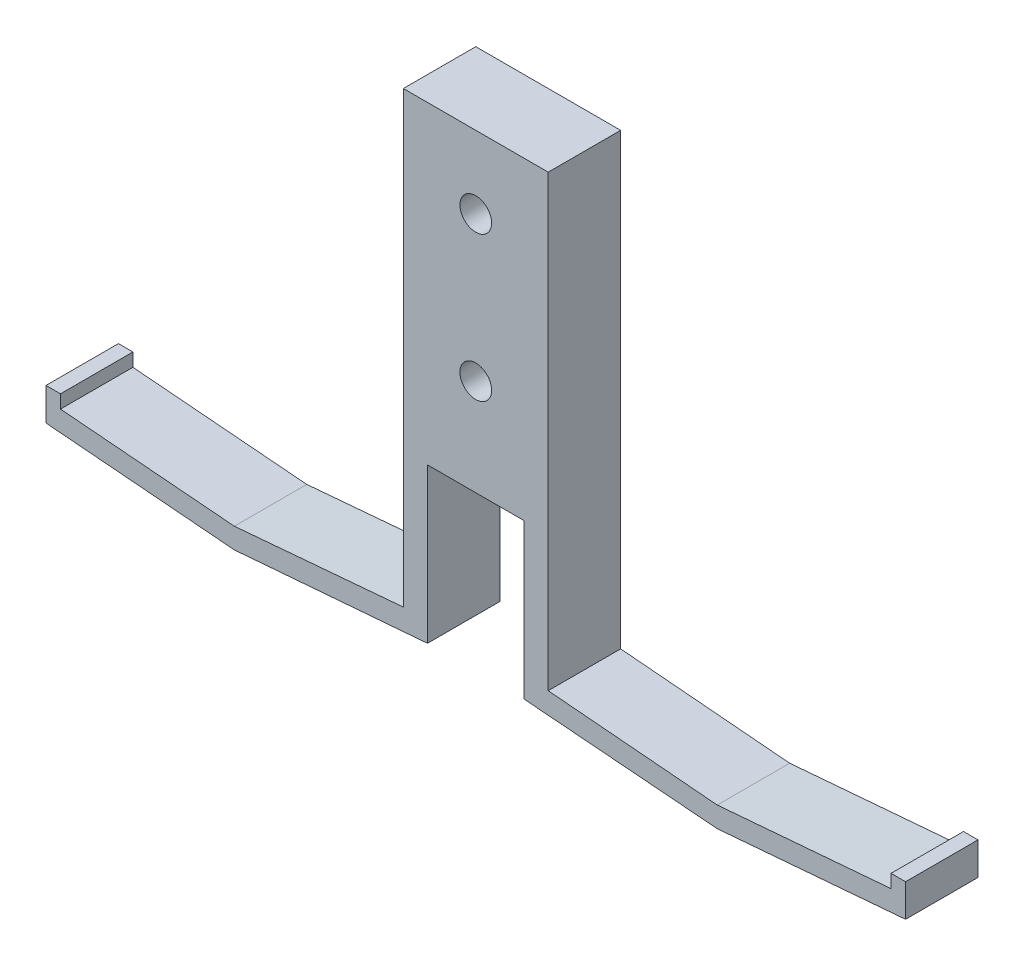
SolidWorks part; units mm, degrees
ref_plane "Front Plane" through (0, 0, 0) normal (0, 0, 1) x (1, 0, 0)
ref_plane "Top Plane" through (0, 0, 0) normal (0, 1, 0) x (1, 0, 0)
ref_plane "Right Plane" through (0, 0, 0) normal (1, 0, 0) x (0, 0, -1)
sketch "Sketch2" plane through (0, 0, 0) normal (0, 0, 1) x (1, 0, 0)
  line L1 (12.7, 0) -> (12.7, -40.64)
  line L2 (12.7, -40.64) -> (63.5, -44.7675)
  line L3 (63.5, -44.7675) -> (113.03, -40.64)
  line L4 (113.03, -40.64) -> (113.03, -32.0675)
  line L5 (109.22, -32.0675) -> (109.22, -35.56)
  line L6 (109.22, -35.56) -> (63.5, -39.37)
  line L19 (113.03, -32.0675) -> (109.22, -32.0675)
  line L20 (0, 125.2351) -> (0, -75.9356) construction
  line L21 (12.7, 0) -> (-12.7, 0)
  line L22 (0, 0) -> (0, 82.55)
  line L23 (19.05, 82.55) -> (-19.05, 82.55)
  line L24 (19.05, 82.55) -> (19.05, 0)
  line L25 (19.05, 0) -> (19.05, -35.56)
  line L26 (19.05, -35.56) -> (63.5, -39.37)
  line L27 (-19.05, 0) -> (-19.05, -35.56)
  line L28 (-19.05, 82.55) -> (-19.05, 0)
  line L29 (-12.7, 0) -> (-12.7, -40.64)
  line L30 (-12.7, -40.64) -> (-63.5, -44.7675)
  line L31 (-63.5, -44.7675) -> (-113.03, -40.64)
  line L32 (-113.03, -40.64) -> (-113.03, -32.0675)
  line L33 (-113.03, -32.0675) -> (-109.22, -32.0675)
  line L34 (-109.22, -32.0675) -> (-109.22, -35.56)
  line L35 (-109.22, -35.56) -> (-63.5, -39.37)
  line L36 (-19.05, -35.56) -> (-63.5, -39.37)
  dimension "D1" = 19.05
  dimension "D2" = 12.7
  dimension "D3" = 35.56
  dimension "D4" = 3.81
  dimension "D5" = 40.64
  dimension "D6" = 3.81
  dimension "D7" = 45.72
  dimension "D8" = 44.45
  dimension "D9" = 12.7
  dimension "D10" = 82.55
extrude "Boss-Extrude1" add sketch "Sketch2" along normal blind 19.05 contours L26 L25 L24 L23 L22 L21 L1 L2 L3 L4 L19 L5 L6 | L27 L36 L35 L34 L33 L32 L31 L30 L29 L21 L22 L23 L28
hole_wizard "21/64 (0.32813) Diameter Hole1" positions "Sketch3" profile "Sketch4" hole size "21/64" standard "ANSI Inch" end condition through all
sketch "Sketch3" plane through (0, 0, 19.05) normal (0, 0, 1) x (1, 0, 0)
  point P0 (0, 25.4)
  point P2 (0, 63.5)
  dimension "D1" = 25.4
  dimension "D2" = 38.1
sketch "Sketch4" plane through (0, 25.4, 19.05) normal (1, 0, 0) x (0, -1, 0)
  line L0 (0, 0) -> (0, 19.05)
  line L1 (0, 19.05) -> (4.1673, 19.05)
  line L2 (4.1673, 19.05) -> (4.1673, 0)
  line L5 (4.1673, 0) -> (0, 0)
  line L11 (0, -6.35) -> (0, 107.95) construction
  dimension "Thru Hole Dia." = 8.3345
  dimension "Thru Hole Depth" = 19.05
